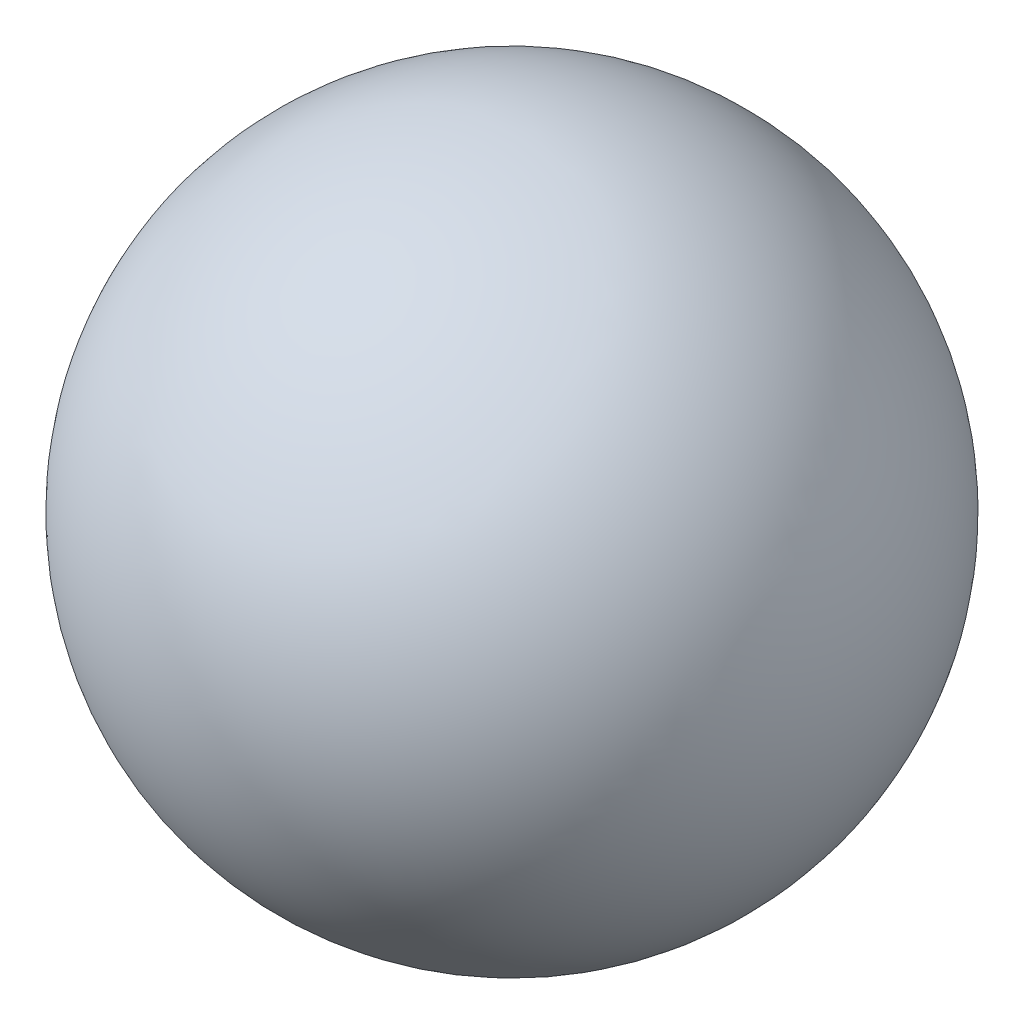
SolidWorks part; units mm, degrees
ref_plane "前视基准面" through (0, 0, 0) normal (0, 0, 1) x (1, 0, 0)
ref_plane "上视基准面" through (0, 0, 0) normal (0, 1, 0) x (1, 0, 0)
ref_plane "右视基准面" through (0, 0, 0) normal (1, 0, 0) x (0, 0, -1)
sketch "草图1" plane through (0, 0, 0) normal (0, 0, 1) x (1, 0, 0)
  line L0 (-240, 0) -> (0, 0) construction
  line L1 (0, 0) -> (-240, 0)
  arc A0 (0, 0) -> (-240, 0) centre (-120, 0) ccw
  dimension "D1" = 240
revolve "旋转1" add sketch "草图1" angle 360 about L0
